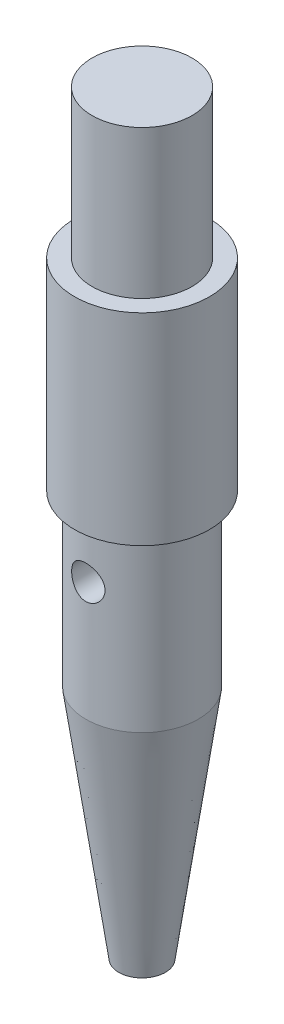
SolidWorks part; units mm, degrees
ref_plane "Front Plane" through (0, 0, 0) normal (0, 0, 1) x (1, 0, 0)
ref_plane "Top Plane" through (0, 0, 0) normal (0, 1, 0) x (1, 0, 0)
ref_plane "Right Plane" through (0, 0, 0) normal (1, 0, 0) x (0, 0, -1)
sketch "Sketch1" plane through (0, 0, 0) normal (0, 0, 1) x (1, 0, 0)
  line L0 (0, 0) -> (4.953, 0)
  line L1 (55, 0) -> (-55, 0) construction
  line L2 (4.953, 0) -> (4.953, -14.6812)
  line L3 (4.953, -14.6812) -> (6.6929, -14.6812)
  line L4 (6.6929, -14.6812) -> (6.6929, -34.671)
  line L5 (6.6929, -34.671) -> (5.5753, -34.671)
  line L6 (5.5753, -34.671) -> (5.5753, -51.5112)
  line L7 (5.5753, -51.5112) -> (2.3114, -74.8792)
  line L8 (2.3114, -74.8792) -> (0, -74.8792)
  line L9 (0, -55) -> (0, 55) construction
  line L10 (0, -74.8792) -> (0, 0)
  dimension "D1" = 4.953
  dimension "D2" = 6.6929
  dimension "D3" = 5.5753
  dimension "D4" = 2.3114
  dimension "D5" = 14.6812
  dimension "D6" = 19.9898
  dimension "D7" = 16.8402
  dimension "D8" = 23.368
revolve "Revolve1" add sketch "Sketch1" angle 360 about L10
sketch "Sketch2" plane through (0, 0, 0) normal (0, 0, 1) x (1, 0, 0)
  line L0 (0, -7.3622) -> (0, 7.3622) construction
  line L1 (-5.5753, -34.671) -> (5.5753, -34.671) construction
  circle A0 centre (0, -39.751) radius 1.6539
  dimension "D1" = 5.08
extrude "Cut-Extrude1" cut sketch "Sketch2" against normal through all and the other way through all
